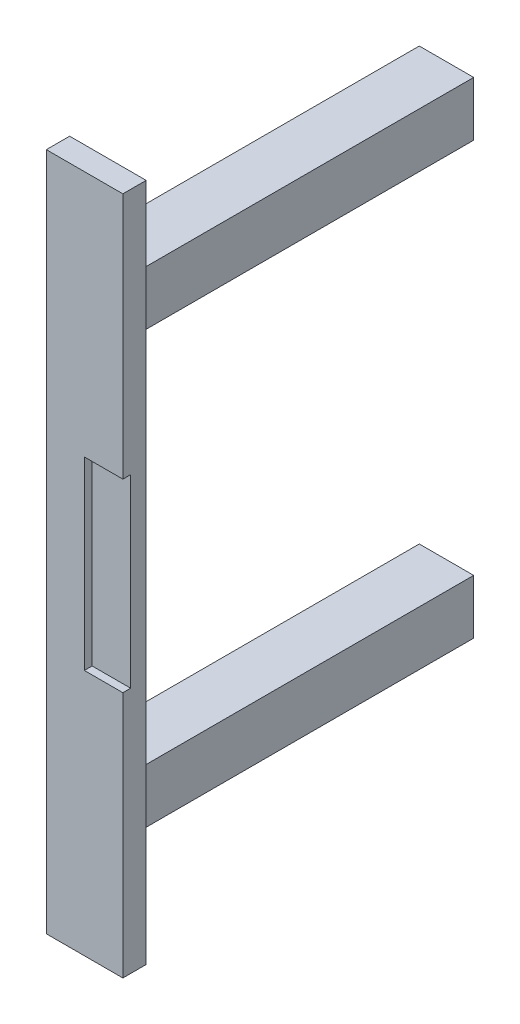
SolidWorks part; units mm, degrees
ref_plane "Front Plane" through (0, 0, 0) normal (0, 0, 1) x (1, 0, 0)
ref_plane "Top Plane" through (0, 0, 0) normal (0, 1, 0) x (1, 0, 0)
ref_plane "Right Plane" through (0, 0, 0) normal (1, 0, 0) x (0, 0, -1)
sketch "Sketch1" plane through (0, 0, 0) normal (0, 1, 0) x (1, 0, 0)
  line L1 (-10, 3) -> (10, 3)
  line L2 (-10, 3) -> (-10, -3)
  line L3 (-10, -3) -> (10, -3)
  line L4 (10, 3) -> (10, -3)
  line L5 (-10, 3) -> (10, -3) construction
  line L6 (-10, -3) -> (10, 3) construction
  point P0 (0, 0)
  dimension "D1" = 6
  dimension "D2" = 20
extrude "Boss-Extrude1" add sketch "Sketch1" along normal blind 174.8
sketch "Sketch2" plane through (0, 0, 3) normal (0, 0, 1) x (1, 0, 0)
  line L0 (10, 174.8) -> (10, 0) construction
  line L1 (-0.2, 111.2) -> (20.2, 111.2)
  line L2 (-0.2, 111.2) -> (-0.2, 63.6)
  line L3 (-0.2, 63.6) -> (20.2, 63.6)
  line L4 (20.2, 111.2) -> (20.2, 63.6)
  line L5 (-0.2, 111.2) -> (20.2, 63.6) construction
  line L6 (-0.2, 63.6) -> (20.2, 111.2) construction
  point P0 (10, 87.4)
  point P7 (0, 0)
  dimension "D1" = 20.4
  dimension "D2" = 47.6
extrude "Cut-Extrude1" cut sketch "Sketch2" against normal blind 2
sketch "Sketch3" plane through (0, 0, -3) normal (0, 0, -1) x (-1, 0, 0)
  line L0 (10, 174.8) -> (10, 0) construction
  line L1 (10, 24.9) -> (-4, 24.9)
  line L2 (10, 24.9) -> (10, 38.9)
  line L3 (10, 38.9) -> (-4, 38.9)
  line L4 (-4, 24.9) -> (-4, 38.9)
  point P6 (0, 0)
  point P7 (0, 0)
  dimension "D1" = 14
  dimension "D2" = 14
extrude "Boss-Extrude2" add sketch "Sketch3" along normal blind 90
ref_plane "Plane1" through (0, 87.4, 0) normal (0, 1, 0) x (1, 0, 0)
mirror "Mirror1" about plane through (0, 87.4, 0) normal (0, 1, 0) of "Boss-Extrude2"
sketch "Sketch4" plane through (0, 0, 0) normal (0, -1, 0) x (1, 0, 0)
  line L0 (-10, 3) -> (10, 3) construction
  line L1 (10, -3) -> (9.7, -3)
  line L2 (10, -3) -> (10, 3)
  line L3 (10, 3) -> (9.7, 3)
  line L4 (9.7, -3) -> (9.7, 3)
  dimension "D1" = 0.3
extrude "Cut-Extrude2" cut sketch "Sketch4" against normal blind 175
